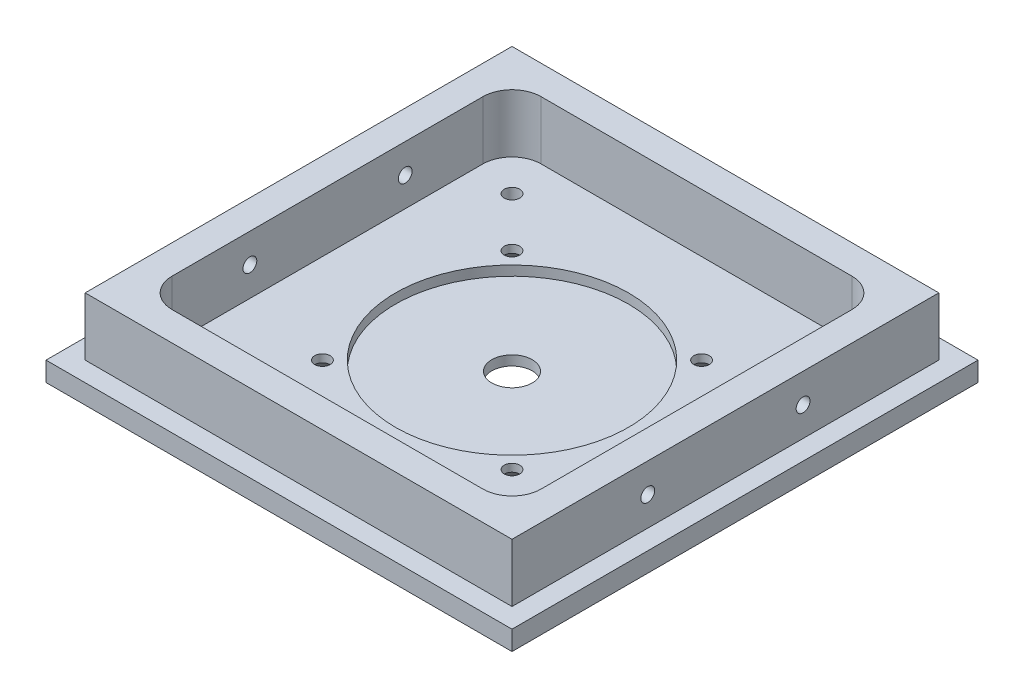
SolidWorks part; units mm, degrees
material "6061-T6 (SS)"
ref_plane "Front Plane" through (0, 0, 0) normal (0, 0, 1) x (1, 0, 0)
ref_plane "Top Plane" through (0, 0, 0) normal (0, 1, 0) x (1, 0, 0)
ref_plane "Right Plane" through (0, 0, 0) normal (1, 0, 0) x (0, 0, -1)
sketch "Sketch1" plane through (0, 0, 0) normal (0, 1, 0) x (1, 0, 0)
  line L1 (-38.1, -38.1) -> (38.1, -38.1)
  line L2 (-38.1, -38.1) -> (-38.1, 38.1)
  line L3 (-38.1, 38.1) -> (38.1, 38.1)
  line L4 (38.1, -38.1) -> (38.1, 38.1)
  line L5 (-38.1, -38.1) -> (38.1, 38.1) construction
  line L6 (-38.1, 38.1) -> (38.1, -38.1) construction
  point P0 (0, 0)
  dimension "D1" = 76.2
  dimension "D2" = 76.2
extrude "Boss-Extrude1" add sketch "Sketch1" along normal blind 3.175
sketch "Sketch2" plane through (0, 3.175, 0) normal (0, 1, 0) x (1, 0, 0)
  line L0 (-38.1, 38.1) -> (-38.1, -38.1) construction
  line L1 (34.8971, -34.8971) -> (-34.8971, -34.8971)
  line L2 (34.8971, -34.8971) -> (34.8971, 34.8971)
  line L3 (34.8971, 34.8971) -> (-34.8971, 34.8971)
  line L4 (-34.8971, -34.8971) -> (-34.8971, 34.8971)
  line L5 (34.8971, -34.8971) -> (-34.8971, 34.8971) construction
  line L6 (34.8971, 34.8971) -> (-34.8971, -34.8971) construction
  line L7 (30.1625, -30.1625) -> (-30.1625, -30.1625)
  line L8 (30.1625, -30.1625) -> (30.1625, 30.1625)
  line L9 (30.1625, 30.1625) -> (-30.1625, 30.1625)
  line L10 (-30.1625, -30.1625) -> (-30.1625, 30.1625)
  line L11 (30.1625, -30.1625) -> (-30.1625, 30.1625) construction
  line L12 (30.1625, 30.1625) -> (-30.1625, -30.1625) construction
  line L14 (38.1, 38.1) -> (-38.1, 38.1) construction
  point P0 (0, 0)
  point P6 (0, 0)
  dimension "D1" = 3.2029
  dimension "D2" = 3.2029
  dimension "D3" = 60.325
extrude "Boss-Extrude2" add sketch "Sketch2" along normal blind 9.525 contours L10 L9 L8 L7
fillet "Fillet1" radius 4.7625 4 edges at (-30.1625, 7.9375, 30.1625) (30.1625, 7.9375, 30.1625) (30.1625, 7.9375, -30.1625) (-30.1625, 7.9375, -30.1625)
sketch "Sketch3" plane through (0, 3.175, 0) normal (0, 1, 0) x (1, 0, 0)
  circle A0 centre (0, 0) radius 19.05
  dimension "D1" = 38.1
extrude "Cut-Extrude1" cut sketch "Sketch3" against normal blind 1.5875
sketch "Sketch4" plane through (0, 1.5875, 0) normal (0, 1, 0) x (1, 0, 0)
  circle A0 centre (0, 0) radius 3.302
  dimension "D1" = 6.604
extrude "Cut-Extrude2" cut sketch "Sketch4" against normal through all
sketch "Sketch5" plane through (0, 3.175, 0) normal (0, 1, 0) x (1, 0, 0)
  line L1 (15.5, -15.5) -> (-15.5, -15.5)
  line L2 (15.5, -15.5) -> (15.5, 15.5)
  line L3 (15.5, 15.5) -> (-15.5, 15.5)
  line L4 (-15.5, -15.5) -> (-15.5, 15.5)
  line L5 (15.5, -15.5) -> (-15.5, 15.5) construction
  line L6 (15.5, 15.5) -> (-15.5, -15.5) construction
  line L7 (23.57, -23.57) -> (-23.57, -23.57)
  line L8 (23.57, -23.57) -> (23.57, 23.57)
  line L9 (23.57, 23.57) -> (-23.57, 23.57)
  line L10 (-23.57, -23.57) -> (-23.57, 23.57)
  line L11 (23.57, -23.57) -> (-23.57, 23.57) construction
  line L12 (23.57, 23.57) -> (-23.57, -23.57) construction
  circle A0 centre (-15.5, 15.5) radius 1.2637
  circle A1 centre (15.5, 15.5) radius 1.2637
  circle A2 centre (15.5, -15.5) radius 1.2637
  circle A3 centre (-15.5, -15.5) radius 1.2637
  point P2 (0, 0)
  point P10 (0, 0)
  dimension "D2" = 2.5273
  dimension "D1" = 31
  dimension "D3" = 47.14
hole_wizard "#39 (0.0995) Diameter Hole1" positions "Sketch7" profile "Sketch6" hole size "#39" standard "ANSI Inch" end condition through all
sketch "Sketch7" plane through (0, 3.175, 0) normal (0, 1, 0) x (1, 0, 0)
  point P0 (15.5, 15.5)
  point P3 (-15.5, 15.5)
  point P6 (-15.5, -15.5)
  point P9 (15.5, -15.5)
  point P12 (-23.57, 23.57)
  point P15 (23.57, 23.57)
  point P18 (23.57, -23.57)
  point P21 (-23.57, -23.57)
sketch "Sketch6" plane through (15.5, 3.175, -15.5) normal (1, 0, 0) x (0, 0, 1)
  line L0 (0, 0) -> (0, 3.175)
  line L1 (0, 3.175) -> (1.2636, 3.175)
  line L2 (1.2636, 3.175) -> (1.2636, 0)
  line L5 (1.2636, 0) -> (0, 0)
  line L11 (0, -6.35) -> (0, 107.95) construction
  dimension "Thru Hole Dia." = 2.5273
  dimension "Thru Hole Depth" = 3.175
sketch "Sketch8" plane through (34.8971, 0, 0) normal (1, 0, 0) x (0, 0, -1)
  line L0 (-38.1, 3.175) -> (38.1, 3.175) construction
  point P0 (-12.7, 7.9375)
  dimension "D1" = 4.7625
  dimension "D2" = 12.7
hole_wizard "#4-40 Tapped Hole1" positions "Sketch10" profile "Sketch9" tap size "#4-40" standard "ANSI Inch"
sketch "Sketch10" plane through (34.8971, 0, 0) normal (1, 0, 0) x (0, 0, -1)
  point P0 (-12.7, 7.9375)
sketch "Sketch9" plane through (34.8971, 7.9375, 12.7) normal (0, 1, 0) x (0, 0, -1)
  line L0 (0, 0) -> (0, 7.2832)
  line L1 (0, 7.2832) -> (1.1303, 6.604)
  line L2 (1.1303, 6.604) -> (1.1303, 0)
  line L5 (1.1303, 0) -> (0, 0)
  line L10 (0, 7.2832) -> (-1.1303, 6.604) construction
  line L11 (0, -6.35) -> (0, 107.95) construction
  dimension "Tap Drill Dia." = 2.2606
  dimension "Tap Drill Depth" = 6.604
  dimension "Drill Angle" = 118
cosmetic thread "Hole Thread1" parameters "D1"=2.4486, "D2"=2.8448
mirror "Mirror1" about plane through (0, 0, 0) normal (0, 0, 1) of "#4-40 Tapped Hole1"
mirror "Mirror2" about plane through (0, 0, 0) normal (1, 0, 0) of "Mirror1", "#4-40 Tapped Hole1"
chamfer "Chamfer1" distance 1.905 angle 41 4 edges at (-15.5, 0, -14.2363) (15.5, 0, -14.2364) (15.5, 0, 16.7636) (-15.5, 0, 16.7637)
equation "\"D2@Sketch2\"=\"D1@Sketch2\""
equation "\"D2@Sketch1\"=\"D1@Sketch1\""
